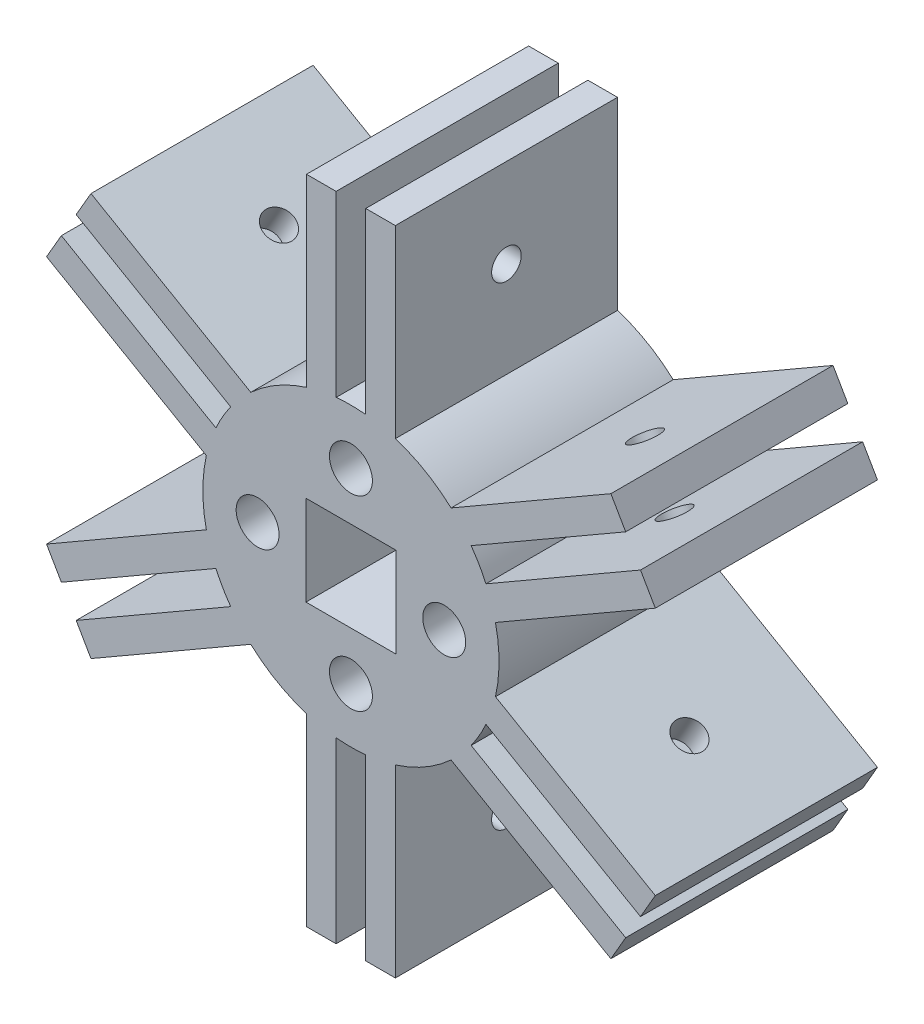
SolidWorks part; units mm, degrees
ref_plane "Front Plane" through (0, 0, 0) normal (0, 0, 1) x (1, 0, 0)
ref_plane "Top Plane" through (0, 0, 0) normal (0, 1, 0) x (1, 0, 0)
ref_plane "Right Plane" through (0, 0, 0) normal (1, 0, 0) x (0, 0, -1)
sketch "Sketch1" plane through (0, 0, 0) normal (0, 0, 1) x (1, 0, 0)
  circle A0 centre (0, 0) radius 10
  dimension "D2" = 20
extrude "Boss-Extrude1" add sketch "Sketch1" along normal mid plane 15
sketch "Sketch4" plane through (0, 0, 7.5) normal (0, 0, 1) x (1, 0, 0)
  line L0 (55, 0) -> (-55, 0) construction
  line L2 (-3, 0) -> (-1, 0)
  line L3 (0, 0) -> (0, 15.8331) construction
  line L4 (-3, 0) -> (-3, 22)
  line L5 (-3, 22) -> (-1, 22)
  line L6 (-1, 0) -> (-1, 22)
  line L7 (0, -55) -> (0, 55) construction
  line L8 (3, 22) -> (1, 22)
  line L9 (1, 0) -> (1, 22)
  line L10 (3, 0) -> (1, 0)
  line L11 (3, 0) -> (3, 22)
  dimension "D1" = 22
  dimension "D3" = 1
extrude "Boss-Extrude3" add sketch "Sketch4" against normal up to surface (15 mm away) up to face at (10, 0, -7.5)
pattern_circular "CirPattern7" count 6 over 360 about axis through (0, 0, 0) along (0, 0, 1) of "Boss-Extrude3"
sketch "Sketch7" plane through (-3, 0, 0) normal (-1, 0, 0) x (0, 0, 1)
  line L0 (-7.5, 22) -> (7.5, 22) construction
  line L1 (-7.5, 9.5394) -> (-7.5, 22) construction
  circle A0 centre (0, 16) radius 1
  circle A1 centre (40, 16) radius 1
  circle A2 centre (80, 16) radius 1
  circle A3 centre (120, 16) radius 1
  circle A4 centre (160, 16) radius 1
  dimension "D1" = 2
  dimension "D2" = 6
  dimension "D3" = 7.5
  dimension "D4" = 5
extrude "Cut-Extrude2" cut sketch "Sketch7" against normal blind 10
pattern_circular "CirPattern9" count 6 over 360 of "Cut-Extrude2"
sketch "Sketch8" plane through (0, 0, 7.5) normal (0, 0, 1) x (1, 0, 0)
  line L2 (-3.0375, 3.0375) -> (3.0375, 3.0375)
  line L3 (-3.0375, 3.0375) -> (-3.0375, -3.0375)
  line L4 (-3.0375, -3.0375) -> (3.0375, -3.0375)
  line L5 (3.0375, 3.0375) -> (3.0375, -3.0375)
  line L6 (-3.0375, 3.0375) -> (3.0375, -3.0375) construction
  line L7 (-3.0375, -3.0375) -> (3.0375, 3.0375) construction
  point P5 (0, 0)
  point P14 (0, 0)
  dimension "D4" = 6.075
  dimension "D5" = 6.075
extrude "Cut-Extrude3" cut sketch "Sketch8" against normal up to next
sketch "Sketch9" plane through (0, 0, 7.5) normal (0, 0, 1) x (1, 0, 0)
  line L0 (8.25, 0) -> (-8.25, 0) construction
  circle A0 centre (6.3, 0) radius 1.45
  circle A1 centre (0, -6.3) radius 1.45
  circle A2 centre (-6.3, 0) radius 1.45
  circle A3 centre (0, 6.3) radius 1.45
  point P14 (0, 0)
  dimension "D1" = 2.9
  dimension "D2" = 6.3
  dimension "D3" = 4
extrude "Cut-Extrude4" cut sketch "Sketch9" against normal blind 10
equation "\"drumDiameter\"= 20mm"
equation "\"D2@Sketch1\"=\"drumDiameter\""
equation "\"drumLength\"= 15"
equation "\"D1@Sketch4\"=\"drumDiameter\"*(0.5+\"drumAbove\")"
equation "\"foamThickness\"= 2"
equation "\"D3@Sketch4\"=\"foamThickness\"/2"
equation "\"drumAbove\"= 0.6"
equation "\"D2@Sketch7\"=\"drumDiameter\"*\"drumAbove\"/2"
equation "\"holderThicc\"= 2"
equation "\"D2@Sketch4\"=\"holderThicc\""
equation "\"D5@Sketch8\"=12.15/2"
equation "\"D1@Boss-Extrude1\"=\"drumLength\""
